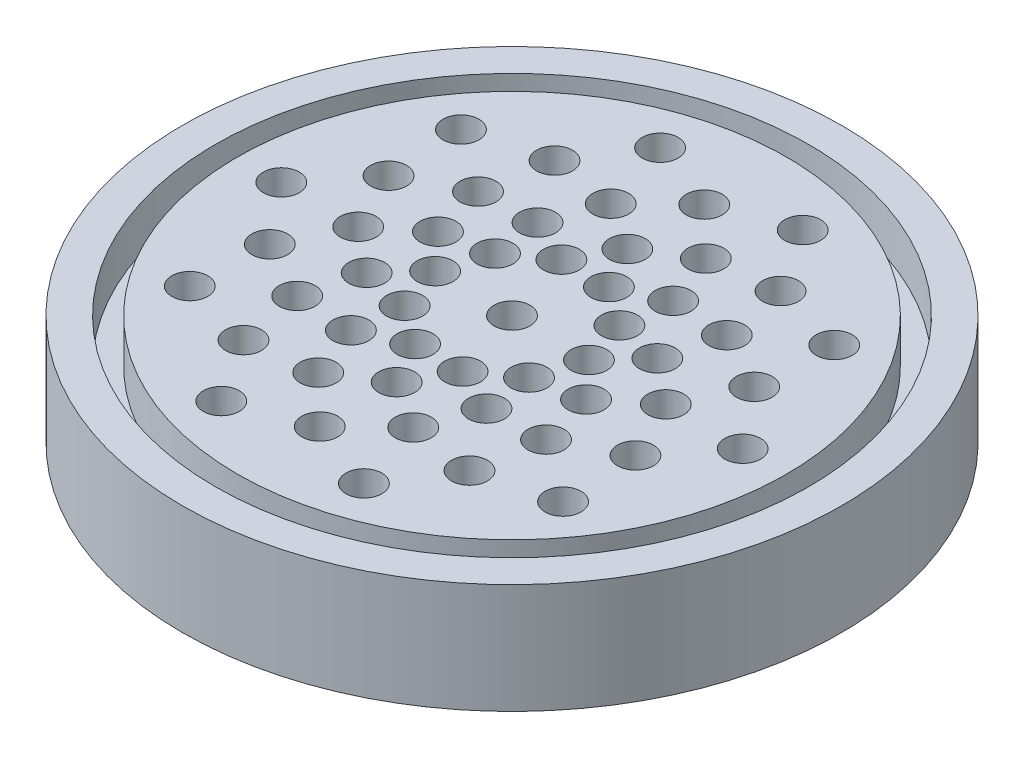
SolidWorks part; units mm, degrees
material "1023 Carbon Steel Sheet (SS)"
ref_plane "Front Plane" through (0, 0, 0) normal (0, 0, 1) x (1, 0, 0)
ref_plane "Top Plane" through (0, 0, 0) normal (0, 1, 0) x (1, 0, 0)
ref_plane "Right Plane" through (0, 0, 0) normal (1, 0, 0) x (0, 0, -1)
sketch "Sketch1" plane through (0, 0, 0) normal (0, 1, 0) x (1, 0, 0)
  circle A0 centre (0, 0) radius 30
  dimension "D1" = 60
extrude "Boss-Extrude1" add sketch "Sketch1" along normal blind 10
sketch "Sketch2" plane through (0, 0, 0) normal (0, -1, 0) x (-1, 0, 0)
  circle A0 centre (0, 0) radius 1.6375
  circle A1 centre (0, 0) radius 1.5875 construction
  dimension "D1" = 0.05
extrude "Cut-Extrude1" cut sketch "Sketch2" against normal through all
pattern_linear "LPattern1" count 4 spacing 7 along (1, 0, 0) of "Cut-Extrude1"
sketch "Sketch3" plane through (0, 0, 0) normal (0, -1, 0) x (1, 0, 0)
  circle A0 centre (0, -10.5) radius 1.6375
  circle A1 centre (0, -10.5) radius 1.5875 construction
  dimension "D1" = 0.05
extrude "Cut-Extrude2" cut sketch "Sketch3" against normal through all
ref_axis "Axis1" through (0, 6.3, 0) along (0, -1, 0)
pattern_linear "LPattern2" count 2 spacing 7 along (0, 0, -1) of "Cut-Extrude2"
pattern_circular "CirPattern1" count 10 over 360 about axis through (0, 0, 0) along (0, 1, 0) of "LPattern1", "LPattern2", "Cut-Extrude2"
hole_wizard "M4x0.7 Tapped Hole1" positions "Sketch4" profile "Sketch5" tap size "M4x0.7" standard "ANSI Metric"
sketch "Sketch4" plane through (0, 0, 0) normal (0, -1, 0) x (-1, 0, 0)
  point P0 (20.2254, -14.6946)
  point P3 (-7.7254, -23.7764)
  point P6 (-25, 0)
  point P9 (-7.7254, 23.7764)
  point P12 (20.2254, 14.6946)
sketch "Sketch5" plane through (-20.2254, 0, 14.6946) normal (1, 0, 0) x (0, 0, -1)
  line L0 (0, 0) -> (0, 4.9914)
  line L1 (0, 4.9914) -> (1.65, 4)
  line L2 (1.65, 4) -> (1.65, 0)
  line L5 (1.65, 0) -> (0, 0)
  line L10 (0, 4.9914) -> (-1.65, 4) construction
  line L11 (0, -6.35) -> (0, 107.95) construction
  dimension "Tap Drill Dia." = 3.3
  dimension "Tap Drill Depth" = 4
  dimension "Drill Angle" = 118
cosmetic thread "Hole Thread1" parameters "D1"=3.8, "D2"=4
cosmetic thread "Hole Thread2" parameters "D1"=3.8, "D2"=4
cosmetic thread "Hole Thread3" parameters "D1"=3.8, "D2"=4
cosmetic thread "Hole Thread4" parameters "D1"=3.8, "D2"=4
cosmetic thread "Hole Thread5" parameters "D1"=3.8, "D2"=4
sketch "Sketch6" plane through (0, 0, 0) normal (0, 0, 1) x (1, 0, 0)
  line L0 (30, 10) -> (-30, 10) construction
  line L1 (27, 10) -> (25, 10)
  line L2 (27, 10) -> (27, 6)
  line L3 (27, 6) -> (25, 6)
  line L4 (25, 10) -> (25, 6)
  line L5 (0, 6.3) -> (0, -0.3) construction
  dimension "D1" = 2
  dimension "D2" = 25
  dimension "D3" = 4
revolve "Cut-Revolve1" cut sketch "Sketch6" angle 360 about axis through (0, 6.3, 0) along (0, -1, 0)
